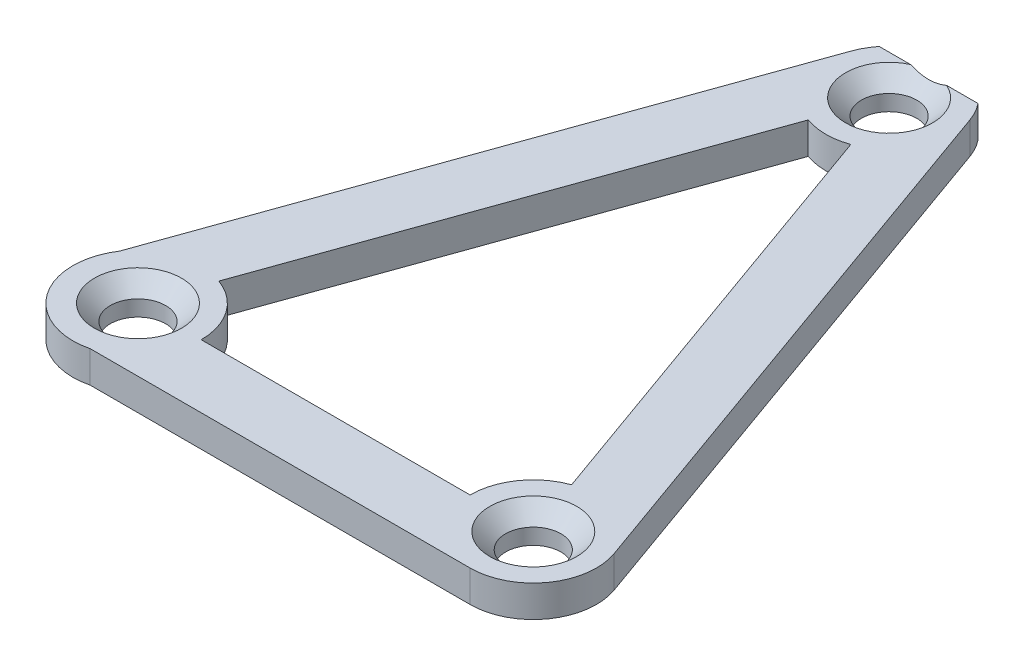
SolidWorks part; units mm, degrees
ref_plane "Ön Düzlem" through (0, 0, 0) normal (0, 0, 1) x (1, 0, 0)
ref_plane "Üst Düzlem" through (0, 0, 0) normal (0, 1, 0) x (1, 0, 0)
ref_plane "Sağ Düzlem" through (0, 0, 0) normal (1, 0, 0) x (0, 0, -1)
sketch "Çizim2" plane through (0, 0, 0) normal (0, 1, 0) x (1, 0, 0)
  line L0 (3.3885, 6.3048) -> (28.3885, 6.3048) construction
  line L1 (15.8885, 6.3048) -> (15.8885, 41.3048) construction
  line L2 (19.6555, 42.6502) -> (32.1555, 7.6502)
  line L3 (28.3885, 2.3048) -> (4.3658, 2.3048)
  line L4 (-0.0498, 8.5705) -> (12.1215, 42.6502)
  line L5 (14.5431, 37.5378) -> (4.7338, 10.0718)
  line L6 (17.2338, 37.5378) -> (27.0431, 10.0718)
  line L7 (7.3885, 6.3048) -> (24.3885, 6.3048)
  circle A0 centre (3.3885, 6.3048) radius 1.75
  circle A1 centre (28.3885, 6.3048) radius 1.75
  circle A2 centre (15.8885, 41.3048) radius 1.75
  arc A3 (14.5431, 37.5378) -> (17.2338, 37.5378) centre (15.8885, 41.3048) ccw
  arc A4 (27.0431, 10.0718) -> (24.3885, 6.3048) centre (28.3885, 6.3048) ccw
  arc A5 (7.3885, 6.3048) -> (4.7338, 10.0718) centre (3.3885, 6.3048) ccw
  arc A6 (28.3885, 2.3048) -> (32.1555, 7.6502) centre (28.3885, 6.3048) ccw
  arc A7 (-0.0498, 8.5705) -> (4.3658, 2.3048) centre (3.3885, 6.3048) ccw
  arc A8 (19.6555, 42.6502) -> (12.1215, 42.6502) centre (15.8885, 41.3048) ccw
  dimension "D1" = 3.5
  dimension "D2" = 3.5
  dimension "D3" = 3.5
  dimension "D6" = 8
  dimension "D7" = 8
  dimension "D8" = 8
  dimension "D4" = 25
  dimension "D5" = 35
  dimension "D9" = 4
  dimension "D10" = 4
  dimension "D11" = 4
extrude "Yükseklik-Ekstrüzyon1" add sketch "Çizim2" along normal blind 2
chamfer "Pah1" distance 1 angle 45 3 edges at (15.8885, 2, -39.5548) (3.3885, 2, -4.5548) (28.3885, 2, -4.5548)
sketch "Çizim3" plane through (0, 2, 0) normal (0, 1, 0) x (1, 0, 0)
  line L0 (15.8885, 45.3048) -> (15.8885, 31.6668) construction
  line L1 (20.8885, 43.8048) -> (10.8885, 43.8048)
  line L2 (20.8885, 43.8048) -> (20.8885, 45.3048)
  line L3 (20.8885, 45.3048) -> (10.8885, 45.3048)
  line L4 (10.8885, 43.8048) -> (10.8885, 45.3048)
  arc A0 (19.6555, 42.6502) -> (12.1215, 42.6502) centre (15.8885, 41.3048) ccw construction
  point P10 (15.8885, 45.3048)
  dimension "D1" = 10
  dimension "D2" = 1.5
extrude "Kes-Ekstrüzyon1" cut sketch "Çizim3" against normal blind 10
